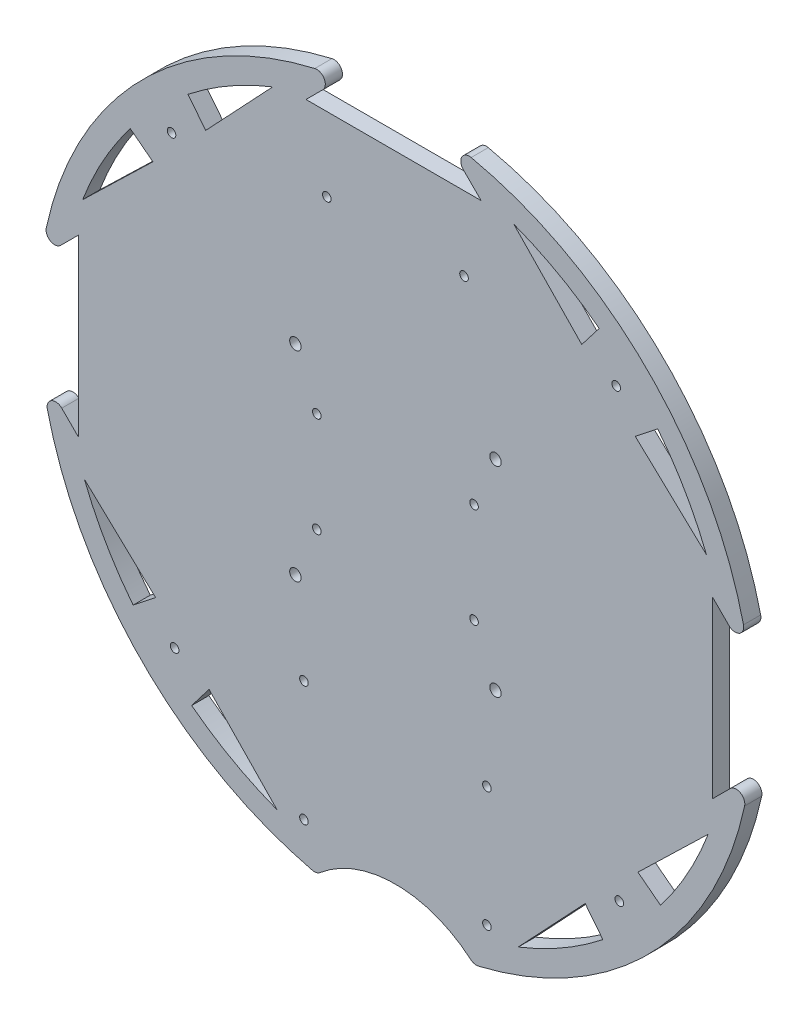
SolidWorks part; units mm, degrees
ref_plane "前视基准面" through (0, 0, 0) normal (0, 0, 1) x (1, 0, 0)
ref_plane "上视基准面" through (0, 0, 0) normal (0, 1, 0) x (1, 0, 0)
ref_plane "右视基准面" through (0, 0, 0) normal (1, 0, 0) x (0, 0, -1)
sketch "草图1" plane through (0, 0, 0) normal (0, 0, 1) x (1, 0, 0)
  line L0 (0, 0) -> (0, -111.7079) construction
  line L1 (0, 35) -> (35, 35) construction
  line L2 (0, 35) -> (-35, 35) construction
  line L3 (35, 35) -> (35, -35) construction
  line L4 (35, -35) -> (-35, -35) construction
  line L5 (-35, -35) -> (-35, 35) construction
  line L6 (0, 35) -> (0, 85) construction
  line L7 (27.5, -17.5) -> (-27.5, -17.5) construction
  line L8 (27.5, -17.5) -> (27.5, 17.5) construction
  line L9 (27.5, 17.5) -> (-27.5, 17.5) construction
  line L10 (-27.5, -17.5) -> (-27.5, 17.5) construction
  line L11 (27.5, -17.5) -> (-27.5, 17.5) construction
  line L12 (27.5, 17.5) -> (-27.5, -17.5) construction
  line L13 (0, 85) -> (24, 85) construction
  line L14 (0, 85) -> (-24, 85) construction
  line L15 (0, 85) -> (0, 110.8472) construction
  line L16 (32, -107.6466) -> (-32, -65.6466) construction
  line L17 (32, -65.6466) -> (-32, -107.6466) construction
  line L18 (0, 110.8472) -> (30, 110.8472)
  line L19 (0, 110.8472) -> (-31.2918, 110.8472)
  line L20 (30, 110.8472) -> (23.7414, 117.1059)
  line L21 (-31.2918, 110.8472) -> (-25.4067, 116.7324)
  line L22 (110.8472, 0) -> (110.8472, -30)
  line L23 (110.8472, 0) -> (110.8472, 31.2918)
  line L24 (110.8472, -30) -> (117.1059, -23.7414)
  line L25 (110.8472, 31.2918) -> (116.7324, 25.4067)
  line L26 (72.5815, -91.7656) -> (66.378, -83.9224)
  line L27 (91.7656, 72.5815) -> (83.9224, 66.378)
  line L28 (83.9224, 66.378) -> (108.8355, 42.94)
  line L29 (65.1975, 84.8427) -> (41.4133, 109.4255)
  line L30 (-110.8472, 0) -> (-110.8472, 30)
  line L31 (-110.8472, 0) -> (-110.8472, -31.2918)
  line L32 (-110.8472, 30) -> (-117.1059, 23.7414)
  line L33 (-110.8472, -31.2918) -> (-116.7324, -25.4067)
  line L34 (0, -110.8472) -> (31.2918, -110.8472) [skipped]
  line L35 (0, -110.8472) -> (-30, -110.8472) [skipped]
  line L36 (-30, -110.8472) -> (-17.01, -123.8372) [skipped]
  line L37 (30.6459, -111.4932) -> (17.6559, -124.4832) [skipped]
  line L38 (71.2907, 92.7719) -> (65.1975, 84.8427)
  line L39 (66.378, -83.9224) -> (42.94, -108.8355)
  line L40 (84.8427, -65.1975) -> (109.4255, -41.4133)
  line L41 (92.7719, -71.2907) -> (84.8427, -65.1975)
  line L42 (-91.7656, -72.5815) -> (-83.9224, -66.378)
  line L43 (-83.9224, -66.378) -> (-108.8355, -42.94)
  line L44 (-65.1975, -84.8427) -> (-41.4133, -109.4255)
  line L45 (-71.2907, -92.7719) -> (-65.1975, -84.8427)
  line L46 (-72.5815, 91.7656) -> (-66.378, 83.9224)
  line L47 (-66.378, 83.9224) -> (-42.94, 108.8355)
  line L48 (-84.8427, 65.1975) -> (-109.4255, 41.4133)
  line L49 (-92.7719, 71.2907) -> (-84.8427, 65.1975)
  circle A0 centre (27.5, 17.5) radius 1.5
  arc A1 (-28.2049, 121.7764) -> (-122.159, 26.4987) centre (0, 0) ccw
  circle A2 centre (35, 35) radius 2
  circle A3 centre (-35, 35) radius 2
  circle A4 centre (-35, -35) radius 2
  circle A5 centre (35, -35) radius 2
  circle A6 centre (-27.5, 17.5) radius 1.5
  circle A7 centre (27.5, -17.5) radius 1.5
  circle A8 centre (-27.5, -17.5) radius 1.5
  circle A9 centre (0, 0) radius 60 construction
  circle A10 centre (32, -65.6466) radius 1.5
  circle A11 centre (-32, -65.6466) radius 1.5
  circle A12 centre (32, -107.6466) radius 1.5
  circle A13 centre (-32, -107.6466) radius 1.5
  circle A14 centre (24, 85) radius 1.5
  circle A15 centre (-24, 85) radius 1.5
  arc A16 (-121.7764, -28.2049) -> (-29.0242, -121.5837) centre (0, 0) ccw
  arc A17 (26.3823, -120.9495) -> (-26.3823, -120.9495) centre (0, -151.9226) ccw
  arc A18 (121.7764, 28.2049) -> (26.4987, 122.159) centre (0, 0) ccw
  arc A19 (29.0242, -121.5837) -> (122.159, -26.4987) centre (0, 0) ccw
  arc A20 (-26.3823, -120.9495) -> (-29.0242, -121.5837) centre (-28.3276, -118.6657) cw
  arc A21 (26.3823, -120.9495) -> (29.0242, -121.5837) centre (28.3276, -118.6657) ccw
  arc A22 (-116.7324, -25.4067) -> (-121.7764, -28.2049) centre (-118.8537, -27.528) ccw
  arc A23 (-117.1059, 23.7414) -> (-122.159, 26.4987) centre (-119.2272, 25.8627) cw
  arc A24 (117.1059, -23.7414) -> (122.159, -26.4987) centre (119.2272, -25.8627) cw
  arc A25 (116.7324, 25.4067) -> (121.7764, 28.2049) centre (118.8537, 27.528) ccw
  arc A26 (-28.2049, 121.7764) -> (-25.4067, 116.7324) centre (-27.528, 118.8537) cw
  arc A27 (26.4987, 122.159) -> (23.7414, 117.1059) centre (25.8627, 119.2272) ccw
  arc A29 (41.4133, 109.4255) -> (71.2907, 92.7719) centre (0, 0) cw
  arc A30 (108.8355, 42.94) -> (91.7656, 72.5815) centre (0, 0) ccw
  circle A32 centre (77.2358, 78.3239) radius 1.5
  arc A33 (42.94, -108.8355) -> (72.5815, -91.7656) centre (0, 0) ccw
  circle A34 centre (78.3239, -77.2358) radius 1.5
  arc A35 (109.4255, -41.4133) -> (92.7719, -71.2907) centre (0, 0) cw
  arc A36 (-108.8355, -42.94) -> (-91.7656, -72.5815) centre (0, 0) ccw
  circle A37 centre (-77.2358, -78.3239) radius 1.5
  arc A38 (-41.4133, -109.4255) -> (-71.2907, -92.7719) centre (0, 0) cw
  arc A39 (-42.94, 108.8355) -> (-72.5815, 91.7656) centre (0, 0) ccw
  circle A40 centre (-78.3239, 77.2358) radius 1.5
  arc A41 (-109.4255, 41.4133) -> (-92.7719, 71.2907) centre (0, 0) cw
  point P22 (0, -86.6466)
  point P53 (27.5, -121.9375)
  point P60 (0, 0)
  point P83 (113.9827, 26.3998)
  point P84 (24.8028, 114.3408)
  point P119 (0, 0)
  dimension "D1" = 4
  dimension "D2" = 3
  dimension "D4" = 4
extrude "凸台-拉伸1" add sketch "草图1" along normal blind 6
